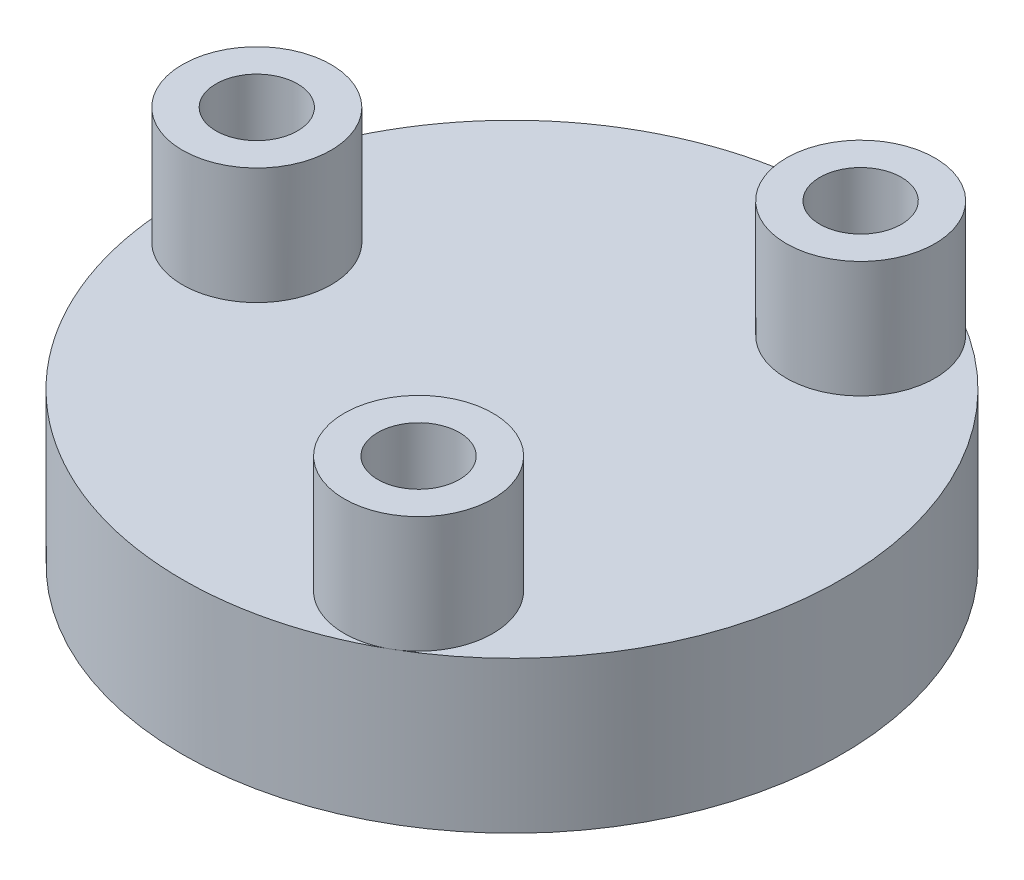
SolidWorks part; units mm, degrees
material "AISI 1020"
ref_plane "Plan de face" through (0, 0, 0) normal (0, 0, 1) x (1, 0, 0)
ref_plane "Plan de dessus" through (0, 0, 0) normal (0, 1, 0) x (1, 0, 0)
ref_plane "Plan de droite" through (0, 0, 0) normal (1, 0, 0) x (0, 0, -1)
sketch "Sketch3" plane through (0, 0, 0) normal (0, 1, 0) x (1, 0, 0)
  line L0 (-55, 0) -> (55, 0) construction
  circle A0 centre (0, 0) radius 28.275
  circle A1 centre (0, 0) radius 21.9 construction
  circle A2 centre (-21.9, 0) radius 6.375 construction
extrude "Boss-Extrude1" add sketch "Sketch3" along normal blind 13
sketch "Sketch4" plane through (0, 13, 0) normal (0, 1, 0) x (1, 0, 0)
  line L0 (-55, 0) -> (55, 0) construction
  circle A0 centre (0, 0) radius 21.9 construction
  circle A1 centre (-21.9, 0) radius 6.375
  circle A2 centre (10.95, 18.966) radius 6.375
  circle A3 centre (10.95, -18.966) radius 6.375
  point P13 (0, 0)
  dimension "D1" = 3
extrude "Boss-Extrude2" add sketch "Sketch4" along normal blind 10
hole_wizard "Dégagement M1.61" positions "Esquisse3" profile "Esquisse5" hole size "M1.6" standard "Ansi Metric" end condition through all
sketch "Esquisse3" plane through (0, 0, 0) normal (0, -1, 0) x (-1, 0, 0)
  point P0 (21.9, 0)
  point P3 (-10.95, 18.966)
  point P6 (-10.95, -18.966)
sketch "Esquisse5" plane through (-21.9, 0, 0) normal (1, 0, 0) x (0, 0, -1)
  line L0 (0, 0) -> (0, 23)
  line L1 (0, 23) -> (3.5, 23)
  line L2 (3.5, 23) -> (3.5, 0)
  line L5 (3.5, 0) -> (0, 0)
  line L11 (0, -6.35) -> (0, 107.95) construction
  dimension "Diamètre du perçage jusqu'au prochain" = 7
  dimension "Profondeur du perçage jusqu'au prochain" = 23
